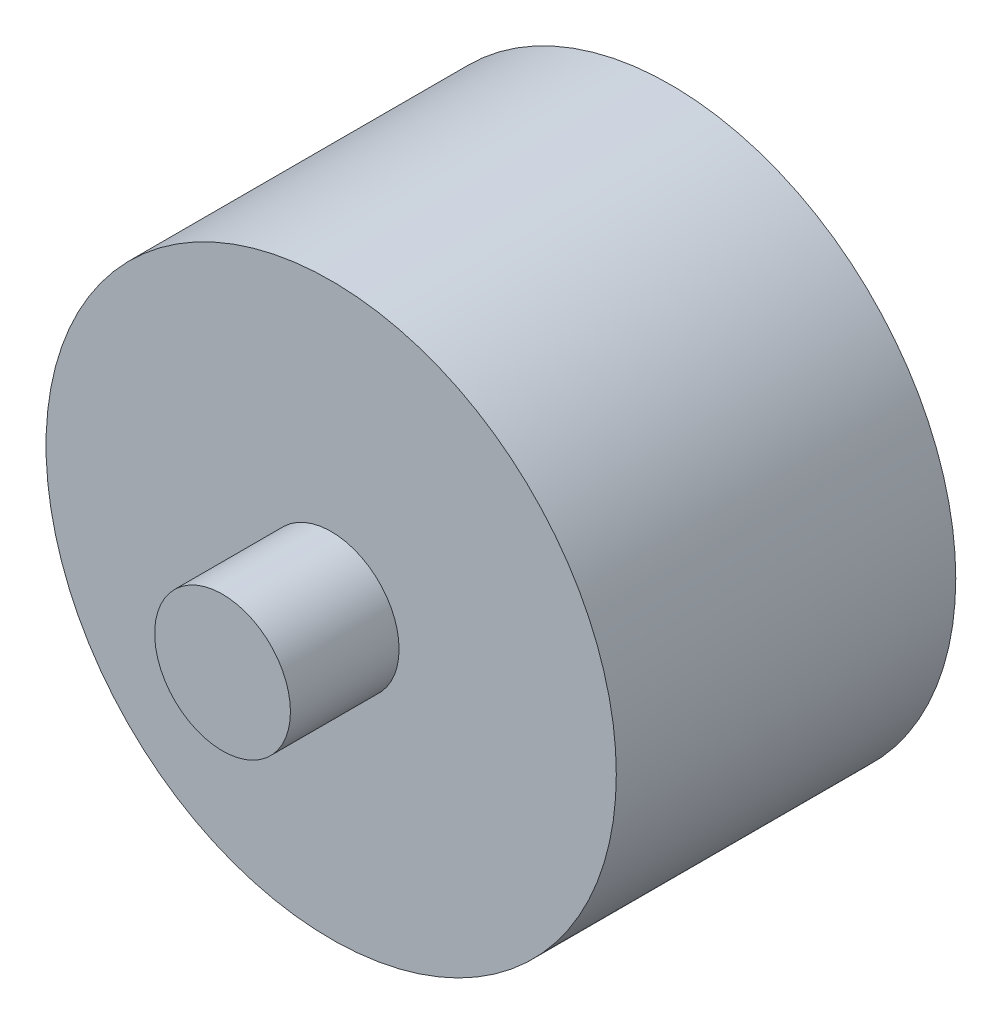
SolidWorks part; units mm, degrees
ref_plane "前视基准面" through (0, 0, 0) normal (0, 0, 1) x (1, 0, 0)
ref_plane "上视基准面" through (0, 0, 0) normal (0, 1, 0) x (1, 0, 0)
ref_plane "右视基准面" through (0, 0, 0) normal (1, 0, 0) x (0, 0, -1)
sketch "草图1" plane through (0, 0, 0) normal (0, 0, 1) x (1, 0, 0)
  circle A0 centre (0, 0) radius 21
  circle A1 centre (0, 0) radius 5
  dimension "D1" = 42
  dimension "D2" = 10
extrude "凸台-拉伸1" add sketch "草图1" along normal blind 25
sketch "草图2" plane through (0, 0, 25) normal (0, 0, 1) x (1, 0, 0)
  circle A0 centre (0, 0) radius 5
extrude "凸台-拉伸2" add sketch "草图2" along normal blind 8 separate body
sketch "草图3" plane through (0, 0, 0) normal (0, 0, -1) x (-1, 0, 0)
  circle A0 centre (0, 0) radius 5
extrude "凸台-拉伸3" add sketch "草图3" along normal blind 8 separate body
